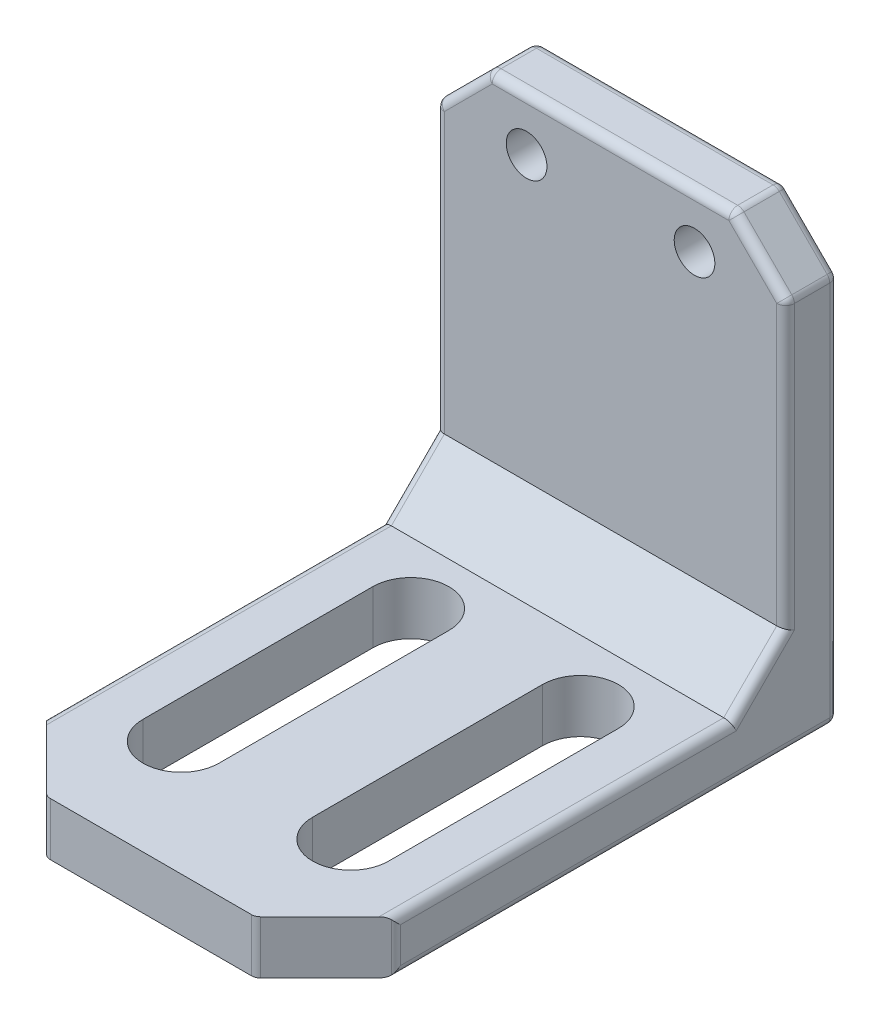
SolidWorks part; units mm, degrees
ref_plane "Front Plane" through (0, 0, 0) normal (0, 0, 1) x (1, 0, 0)
ref_plane "Top Plane" through (0, 0, 0) normal (0, 1, 0) x (1, 0, 0)
ref_plane "Right Plane" through (0, 0, 0) normal (1, 0, 0) x (0, 0, -1)
sketch "Sketch1" plane through (0, 0, 0) normal (0, 0, 1) x (1, 0, 0)
  line L0 (0, 13.7877) -> (0, -11.2123) construction
  line L1 (-9.9, -11.2123) -> (9.9, -11.2123)
  line L2 (-9.9, -11.2123) -> (-9.9, 13.7877)
  line L3 (-9.9, 13.7877) -> (9.9, 13.7877)
  line L4 (9.9, -11.2123) -> (9.9, 13.7877)
  circle A0 centre (-4.75, 10.7877) radius 1.15
  circle A1 centre (4.75, 10.7877) radius 1.15
  point P0 (0, 0)
  dimension "D3" = 2.3
  dimension "D1" = 19.8
  dimension "D2" = 25
  dimension "D4" = 4.75
  dimension "D5" = 22
extrude "Boss-Extrude1" add sketch "Sketch1" along normal blind 3
sketch "Sketch2" plane through (0, 0, 3) normal (0, 0, 1) x (1, 0, 0)
  line L0 (9.9, -11.2123) -> (9.9, 13.7877) construction
  line L1 (-9.9, -11.2123) -> (9.9, -11.2123)
  line L2 (-9.9, -11.2123) -> (-9.9, -8.2123)
  line L3 (-9.9, -8.2123) -> (9.9, -8.2123)
  line L4 (9.9, -11.2123) -> (9.9, -8.2123)
  dimension "D1" = 3
extrude "Boss-Extrude2" add sketch "Sketch2" along normal blind 26
chamfer "Chamfer1" distance 3 angle 45 3 edges at (9.9, 13.7877, 1.5) (-9.9, 13.7877, 1.5) (0, -8.2123, 3)
sketch "Sketch4" plane through (0, -8.2123, 0) normal (0, 1, 0) x (1, 0, 0)
  line L0 (0, -6) -> (0, -29) construction
  line L1 (9.9, -6) -> (-9.9, -6) construction
  line L2 (9.9, -29) -> (-9.9, -29) construction
  line L5 (4.7971, -13.9889) -> (4.7971, -22.5) construction
  line L6 (4.7971, -22.5) -> (4.7971, -9.5) construction
  line L7 (2.6471, -22.5) -> (2.6471, -9.5)
  line L8 (6.9471, -22.5) -> (6.9471, -9.5)
  line L9 (-4.7971, -13.9889) -> (-4.7971, -22.5) construction
  line L10 (-4.7971, -22.5) -> (-4.7971, -9.5) construction
  line L11 (-2.6471, -22.5) -> (-2.6471, -9.5)
  line L12 (-6.9471, -22.5) -> (-6.9471, -9.5)
  arc A2 (2.6471, -22.5) -> (6.9471, -22.5) centre (4.7971, -22.5) ccw
  arc A3 (6.9471, -9.5) -> (2.6471, -9.5) centre (4.7971, -9.5) ccw
  arc A4 (-2.6471, -22.5) -> (-6.9471, -22.5) centre (-4.7971, -22.5) cw
  arc A5 (-6.9471, -9.5) -> (-2.6471, -9.5) centre (-4.7971, -9.5) cw
  point P12 (4.7971, -16)
  point P21 (-4.7971, -16)
  dimension "D1" = 13
  dimension "D2" = 4.3
  dimension "D3" = 13
extrude "Cut-Extrude1" cut sketch "Sketch4" against normal blind 15
chamfer "Chamfer2" distance 4 angle 45 2 edges at (9.9, -9.7123, 29) (-9.9, -9.7123, 29)
fillet "Fillet2" radius 0.5 27 edges at (-8.4, 12.2877, 3) (-9.9, 10.7877, 1.5) (-9.9, 2.7877, 3) (-9.9, -6.7123, 4.5) (-9.9, -8.2123, 15.5) (-9.9, -9.7123, 25) (-9.9, -11.2123, 12.5) (9.9, -6.7123, 4.5) (9.9, 2.7877, 3) (9.9, -11.2123, 12.5) (9.9, -9.7123, 25) (9.9, -8.2123, 15.5) (3.6, 10.7877, 0) (-8.4, 12.2877, 0) (-9.9, -0.2123, 0) (0, -11.2123, 0) (9.9, -0.2123, 0) (-3.6, 10.7877, 0) (8.4, 12.2877, 0) (9.9, 10.7877, 1.5) (8.4, 12.2877, 3) (-6.9, 13.7877, 1.5) (0, 13.7877, 0) (6.9, 13.7877, 1.5) (0, 13.7877, 3) (5.9, -9.7123, 29) (-5.9, -9.7123, 29)
